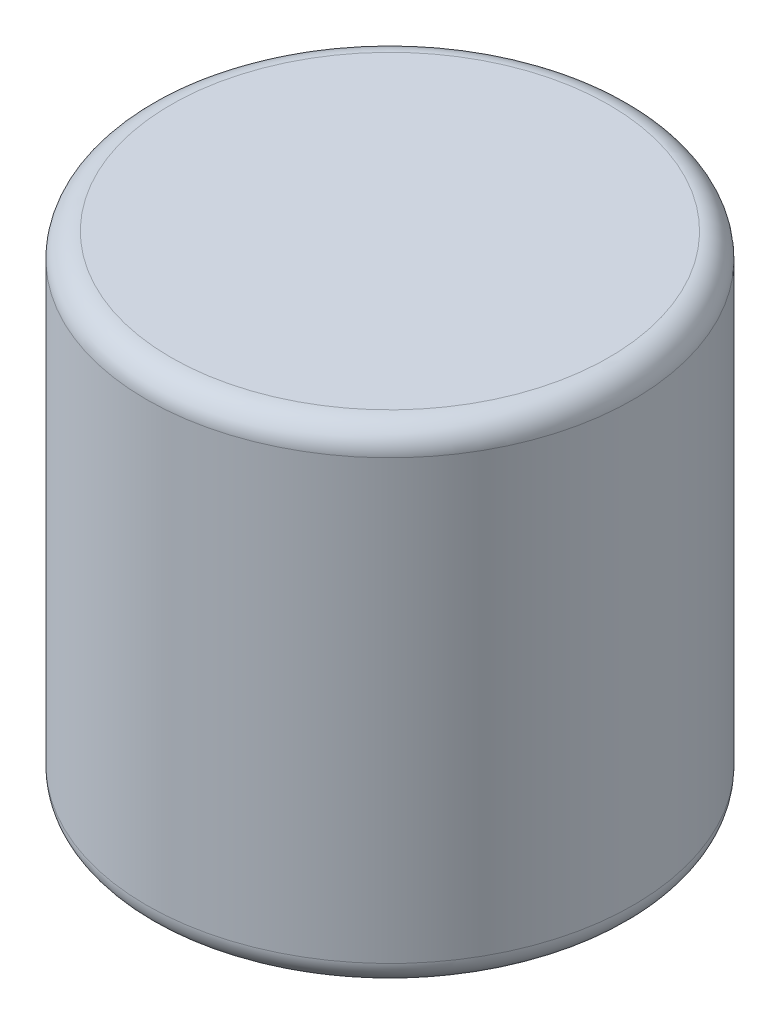
SolidWorks part; units mm, degrees
ref_plane "Front Plane" through (0, 0, 0) normal (0, 0, 1) x (1, 0, 0)
ref_plane "Top Plane" through (0, 0, 0) normal (0, 1, 0) x (1, 0, 0)
ref_plane "Right Plane" through (0, 0, 0) normal (1, 0, 0) x (0, 0, -1)
sketch "Sketch1" plane through (0, 0, 0) normal (0, 1, 0) x (1, 0, 0)
  circle A0 centre (0, 0) radius 5
  dimension "D1" = 10
extrude "Boss-Extrude1" add sketch "Sketch1" along normal blind 10
fillet "Fillet1" radius 0.5 2 edges at (0, 0, 5) (0, 10, 5)
